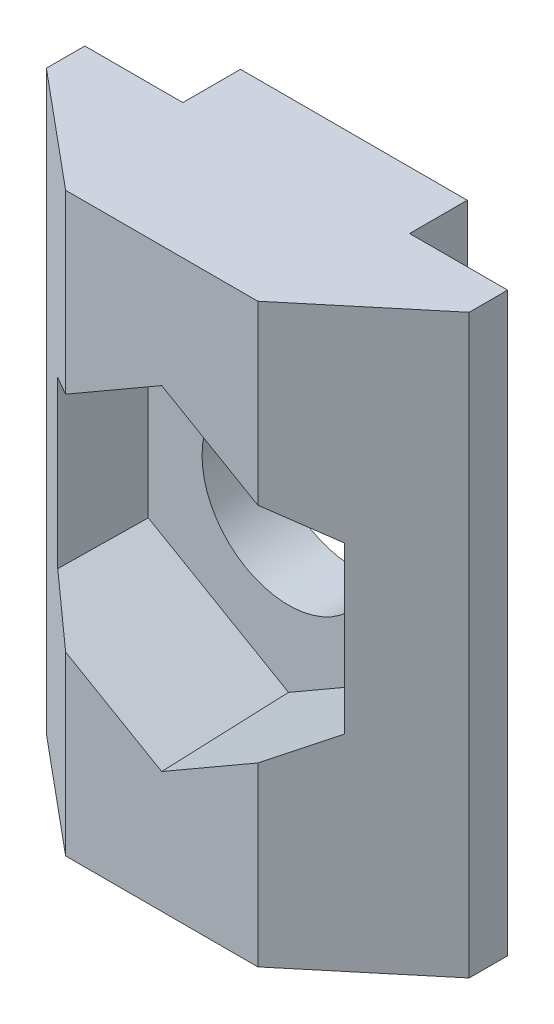
SolidWorks part; units mm, degrees
material "ABS"
ref_plane "Front Plane" through (0, 0, 0) normal (0, 0, 1) x (1, 0, 0)
ref_plane "Top Plane" through (0, 0, 0) normal (0, 1, 0) x (1, 0, 0)
ref_plane "Right Plane" through (0, 0, 0) normal (1, 0, 0) x (0, 0, -1)
sketch "Sketch1" plane through (0, 0, 0) normal (0, 1, 0) x (1, 0, 0)
  line L0 (-2.95, 0) -> (2.95, 0)
  line L1 (2.95, 0) -> (2.95, -1.5)
  line L2 (2.95, -1.5) -> (5.5, -1.5)
  line L3 (5.5, -1.5) -> (5.5, -2.5)
  line L4 (5.5, -2.5) -> (2.5, -5)
  line L5 (2.5, -5) -> (-2.5, -5)
  line L6 (-2.5, -5) -> (-5.5, -2.5)
  line L7 (-5.5, -2.5) -> (-5.5, -1.5)
  line L8 (-5.5, -1.5) -> (-2.95, -1.5)
  line L9 (-2.95, -1.5) -> (-2.95, 0)
  line L10 (0, 0) -> (0, -5) construction
  dimension "D1" = 5.9
  dimension "D2" = 5
  dimension "D3" = 1
  dimension "D4" = 2.55
  dimension "D5" = 1.5
  dimension "D6" = 5
extrude "Boss-Extrude1" add sketch "Sketch1" along normal mid plane 15
sketch "Sketch2" plane through (0, 0, 5) normal (0, 0, 1) x (1, 0, 0)
  circle A0 centre (0, 0) radius 2.25
  dimension "D1" = 4.5
extrude "Cut-Extrude1" cut sketch "Sketch2" against normal through all
sketch "Sketch3" plane through (0, 0, 5) normal (0, 0, 1) x (1, 0, 0)
  line L1 (0, 4.2147) -> (-3.65, 2.1073)
  line L2 (-3.65, 2.1073) -> (-3.65, -2.1073)
  line L3 (-3.65, -2.1073) -> (0, -4.2147)
  line L4 (0, -4.2147) -> (3.65, -2.1073)
  line L5 (3.65, -2.1073) -> (3.65, 2.1073)
  line L6 (3.65, 2.1073) -> (0, 4.2147)
  circle A0 centre (0, 0) radius 3.65 construction
  dimension "D1" = 7.3
extrude "Cut-Extrude2" cut sketch "Sketch3" along normal through all draft 2 from offset 3.3
